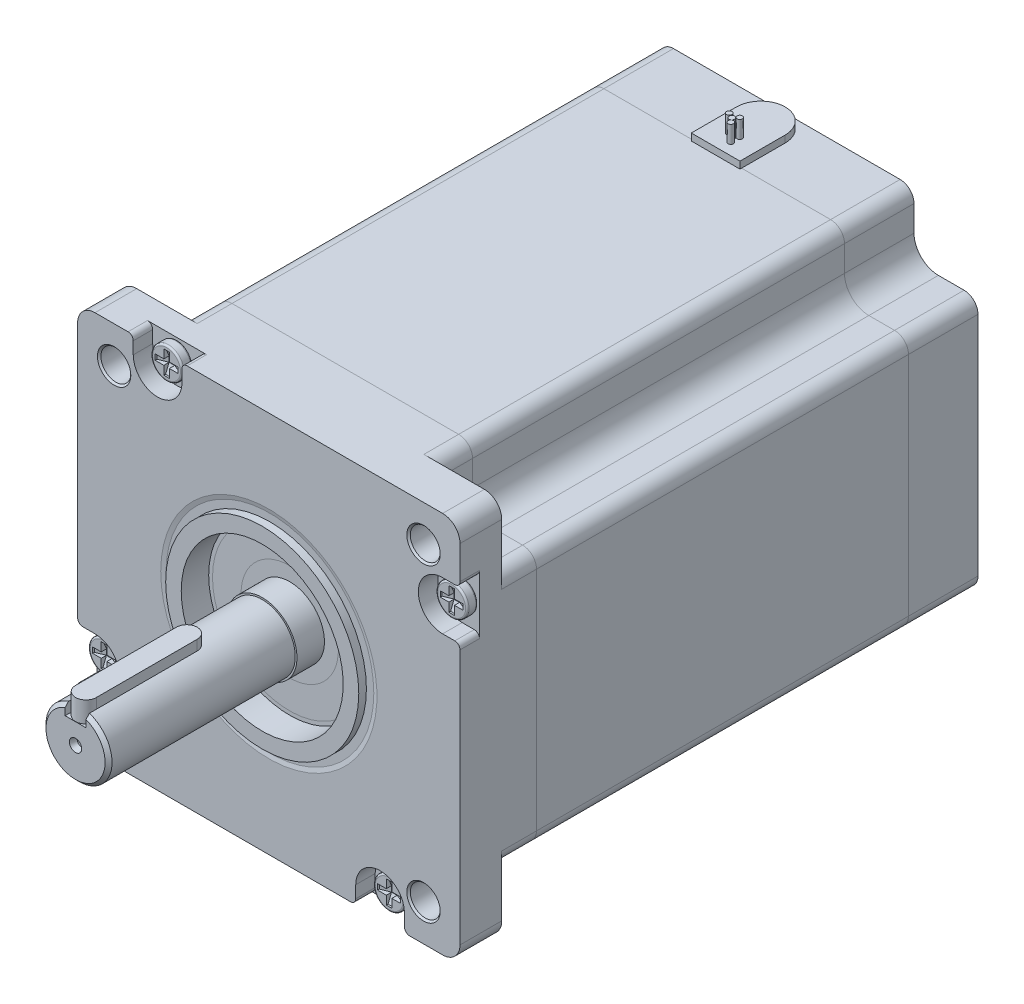
SolidWorks part; units mm, degrees
ref_plane "Front Plane" through (0, 0, 0) normal (0, 0, 1) x (1, 0, 0)
ref_plane "Top Plane" through (0, 0, 0) normal (0, 1, 0) x (1, 0, 0)
ref_plane "Right Plane" through (0, 0, 0) normal (1, 0, 0) x (0, 0, -1)
sketch "Sketch1" plane through (0, 0, 0) normal (0, 0, 1) x (1, 0, 0)
  line L1 (50, -55) -> (-50, -55)
  line L2 (55, -50) -> (55, 50)
  line L3 (50, 55) -> (-50, 55)
  line L4 (-55, -50) -> (-55, 50)
  line L5 (55, -55) -> (-55, 55) construction
  line L6 (55, 55) -> (-55, -55) construction
  arc A0 (50, -55) -> (55, -50) centre (50, -50) ccw
  arc A1 (-50, -55) -> (-55, -50) centre (-50, -50) cw
  arc A2 (55, 50) -> (50, 55) centre (50, 50) ccw
  arc A3 (-50, 55) -> (-55, 50) centre (-50, 50) ccw
  circle A4 centre (-44.5, 44.5) radius 4.3
  circle A5 centre (44.5, 44.5) radius 4.3
  circle A6 centre (-44.5, -44.5) radius 4.3
  circle A7 centre (44.5, -44.5) radius 4.3
  point P0 (0, 0)
  dimension "D3" = 5
  dimension "D4" = 8.6
  dimension "D5" = 89
  dimension "D6" = 89
  dimension "D1" = 110
  dimension "D2" = 110
  dimension "D7" = 44.5
  dimension "D8" = 44.5
extrude "Boss-Extrude1" add sketch "Sketch1" along normal blind 22
sketch "Sketch2" plane through (0, 0, 0) normal (0, 0, -1) x (-1, 0, 0)
  line L0 (-51, 36.6) -> (-43.6, 36.6)
  line L1 (-36.6, 43.6) -> (-36.6, 51)
  line L2 (-32.6, 55) -> (-50, 55)
  line L3 (-55, 50) -> (-55, 32.6)
  line L4 (-50, -55) -> (50, -55)
  line L5 (55, -50) -> (55, 50)
  line L6 (50, 55) -> (-50, 55)
  line L7 (-55, 50) -> (-55, -50)
  line L8 (0, 55) -> (0, -55) construction
  line L9 (-50, 55) -> (50, 55) construction
  line L10 (50, -55) -> (-50, -55) construction
  line L11 (0, 0) -> (-55, 0) construction
  line L12 (-55, -50) -> (-55, 50) construction
  line L13 (55, 50) -> (55, 32.6)
  line L14 (32.6, 55) -> (50, 55)
  line L15 (36.6, 43.6) -> (36.6, 51)
  line L16 (51, 36.6) -> (43.6, 36.6)
  line L17 (51, -36.6) -> (43.6, -36.6)
  line L18 (36.6, -43.6) -> (36.6, -51)
  line L19 (32.6, -55) -> (50, -55)
  line L20 (55, -50) -> (55, -32.6)
  line L21 (-55, -50) -> (-55, -32.6)
  line L22 (-32.6, -55) -> (-50, -55)
  line L23 (-36.6, -43.6) -> (-36.6, -51)
  line L24 (-51, -36.6) -> (-43.6, -36.6)
  arc A0 (-43.6, 36.6) -> (-36.6, 43.6) centre (-43.6, 43.6) ccw
  arc A1 (-51, 36.6) -> (-55, 32.6) centre (-51, 32.6) ccw
  arc A2 (-36.6, 51) -> (-32.6, 55) centre (-32.6, 51) cw
  arc A3 (50, 55) -> (55, 50) centre (50, 50) cw
  arc A4 (-55, -50) -> (-50, -55) centre (-50, -50) ccw
  arc A5 (50, -55) -> (55, -50) centre (50, -50) ccw
  arc A6 (55, 50) -> (50, 55) centre (50, 50) ccw
  arc A7 (-50, 55) -> (-55, 50) centre (-50, 50) ccw
  arc A8 (36.6, 51) -> (32.6, 55) centre (32.6, 51) ccw
  arc A9 (51, 36.6) -> (55, 32.6) centre (51, 32.6) cw
  arc A10 (43.6, 36.6) -> (36.6, 43.6) centre (43.6, 43.6) cw
  arc A11 (-50, 55) -> (-55, 50) centre (-50, 50) ccw
  arc A12 (43.6, -36.6) -> (36.6, -43.6) centre (43.6, -43.6) ccw
  arc A13 (51, -36.6) -> (55, -32.6) centre (51, -32.6) ccw
  arc A14 (36.6, -51) -> (32.6, -55) centre (32.6, -51) cw
  arc A15 (50, -55) -> (55, -50) centre (50, -50) ccw
  arc A16 (-50, -55) -> (-55, -50) centre (-50, -50) cw
  arc A17 (-36.6, -51) -> (-32.6, -55) centre (-32.6, -51) ccw
  arc A18 (-51, -36.6) -> (-55, -32.6) centre (-51, -32.6) cw
  arc A19 (-43.6, -36.6) -> (-36.6, -43.6) centre (-43.6, -43.6) cw
  point P17 (-36.6, 36.6)
  point P20 (-55, 36.6)
  point P43 (55, 36.6)
  point P44 (36.6, 36.6)
  point P54 (36.6, -36.6)
  point P55 (55, -36.6)
  point P65 (-55, -36.6)
  point P66 (-36.6, -36.6)
  dimension "D4" = 7
  dimension "D5" = 4
  dimension "D3" = 18.4
  dimension "D1" = 0
extrude "Cut-Extrude1" cut sketch "Sketch2" against normal blind 10
chamfer "Chamfer1" distance 0.5 angle 45 8 edges at (-48.8, -44.5, 10) (-40.2, -44.5, 22) (48.8, -44.5, 22) (48.8, -44.5, 10) (40.2, 44.5, 10) (48.8, 44.5, 22) (-40.2, 44.5, 22) (-40.2, 44.5, 10)
sketch "Sketch3" plane through (0, 0, 22) normal (0, 0, 1) x (1, 0, 0)
  line L0 (50, 55) -> (-50, 55) construction
  line L1 (-39, 50) -> (-39, 60.5998)
  line L2 (-39, 60.5998) -> (-25, 60.5998)
  line L3 (-25, 60.5998) -> (-25, 50)
  line L4 (-55, 50) -> (-55, -50) construction
  arc A0 (-39, 50) -> (-25, 50) centre (-32, 50) ccw
  dimension "D2" = 14
  dimension "D1" = 5
  dimension "D3" = 16
extrude "Cut-Extrude2" cut sketch "Sketch3" against normal blind 5.6
fillet "Fillet1" radius 1.5 2 edges at (-39, 55, 19.2) (-25, 55, 19.2)
sketch "Sketch6" plane through (0, 0, 22) normal (0, 0, 1) x (1, 0, 0)
  circle A0 centre (0, 0) radius 27.775
  dimension "D1" = 55.55
extrude "Boss-Extrude2" add sketch "Sketch6" along normal blind 1.9
sketch "Sketch7" plane through (0, 0, 0) normal (1, 0, 0) x (0, 0, -1)
  line L0 (0, 0) -> (-55.0013, 0) construction
  line L1 (-22, 27.775) -> (-21.7, 27.775)
  line L2 (-22, -50) -> (-22, 50) construction
  line L3 (-22, 27.775) -> (-22, -27.775) construction
  line L4 (-21.7, 27.775) -> (-21.7, 29.9)
  line L5 (-21.7, 29.9) -> (-22, 31.1)
  line L6 (-22, 31.1) -> (-22, 27.775)
  line L7 (-23.9, 27.775) -> (-23.9, -27.775) construction
  line L8 (-23.9, 23.3) -> (-16, 23.3)
  line L9 (-16, 23.3) -> (-16, 10)
  line L10 (-16, 10) -> (-23.9, 10)
  line L11 (-23.9, 10) -> (-23.9, 23.3)
  dimension "D1" = 55.55
  dimension "D2" = 2.2
  dimension "D3" = 59.8
  dimension "D4" = 62.2
  dimension "D5" = 46.6
  dimension "D6" = 20
  dimension "D7" = 7.9
revolve "Cut-Revolve1" cut sketch "Sketch7" angle 360 about L0
sketch "Sketch8" plane through (0, 0, 16) normal (0, 0, 1) x (1, 0, 0)
  circle A0 centre (0, 0) radius 14
  circle A1 centre (0, 0) radius 22.2
  dimension "D1" = 28
  dimension "D2" = 44.4
split line "Split Line1"
sketch "Sketch9" plane through (0, 0, 23.9) normal (0, 0, 1) x (1, 0, 0)
  circle A0 centre (0, 0) radius 9.5
  dimension "D1" = 19
extrude "Boss-Extrude3" add sketch "Sketch9" along normal blind 53.7
chamfer "Chamfer2" distance 1 angle 45 1 edges at (9.5, 0, 77.6)
sketch "Sketch11" plane through (0, 0, 77.6) normal (0, 0, 1) x (1, 0, 0)
  line L1 (3, 13.1) -> (-3, 13.1)
  line L2 (3, 13.1) -> (3, 5.9)
  line L3 (3, 5.9) -> (-3, 5.9)
  line L4 (-3, 13.1) -> (-3, 5.9)
  line L5 (3, 13.1) -> (-3, 5.9) construction
  line L6 (3, 5.9) -> (-3, 13.1) construction
  circle A0 centre (0, 0) radius 9.5 construction
  circle A1 centre (0, 0) radius 9.5 construction
  point P0 (0, 9.5)
  dimension "D1" = 6
  dimension "D2" = 3.6
extrude "Cut-Extrude3" cut sketch "Sketch11" against normal blind 35
fillet "Fillet2" radius 2.95 2 edges at (-3, 7.4569, 42.6) (3, 7.4569, 42.6)
sketch "Sketch12" plane through (0, 5.9, 0) normal (0, 1, 0) x (1, 0, 0)
  line L0 (-0.05, -45.55) -> (-0.05, -74.55) construction
  line L1 (2.95, -45.55) -> (2.95, -74.55)
  line L2 (-3.05, -45.55) -> (-3.05, -74.55)
  arc A0 (2.95, -45.55) -> (-3.05, -45.55) centre (-0.05, -45.55) ccw
  arc A1 (-3.05, -74.55) -> (2.95, -74.55) centre (-0.05, -74.55) ccw
  point P3 (-0.05, -60.05)
  dimension "D2" = 3
  dimension "D1" = 29
extrude "Boss-Extrude4" add sketch "Sketch12" along normal blind 6 separate body
sketch "Sketch13" plane through (0, 0, 77.6) normal (0, 0, 1) x (1, 0, 0)
  circle A0 centre (0, 0) radius 1.2695
extrude "Cut-Extrude4" cut sketch "Sketch13" against normal blind 5
chamfer "Chamfer3" distance 0.5 angle 74 1 edges at (1.2695, 0, 77.6)
pattern_circular "CirPattern2" count 4 over 360 about axis through (0, 0, 0) along (0, 0, 1) of "Cut-Extrude2"
fillet "Fillet3" radius 1.5 6 edges at (-55, -39, 19.2) (-55, -25, 19.2) (39, -55, 19.2) (25, -55, 19.2) (55, 25, 19.2) (55, 39, 19.2)
sketch "Sketch14" plane through (0, 0, 16.4) normal (0, 0, 1) x (1, 0, 0)
  circle A0 centre (-32, 50) radius 4.5
  dimension "D1" = 9
extrude "Boss-Extrude5" add sketch "Sketch14" along normal blind 3 separate body
fillet "Fillet4" radius 0.5 2 edges at (-27.5, 50, 16.4) (-27.5, 50, 19.4)
sketch "Sketch15" plane through (0, 0, 19.4) normal (0, 0, 1) x (1, 0, 0)
  line L0 (-31.2058, 50.8067) -> (-28.6738, 50.8067)
  line L1 (-32.7942, 46.7257) -> (-31.2058, 46.7257)
  line L2 (-32.7942, 46.7257) -> (-32.7942, 49.1933)
  line L3 (-32.7942, 53.2743) -> (-31.2058, 53.2743)
  line L4 (-31.2058, 46.7257) -> (-31.2058, 49.1933)
  line L7 (-35.3262, 49.1933) -> (-32.7942, 49.1933)
  line L8 (-35.3262, 49.1933) -> (-35.3262, 50.8067)
  line L9 (-35.3262, 50.8067) -> (-32.7942, 50.8067)
  line L10 (-28.6738, 49.1933) -> (-28.6738, 50.8067)
  line L15 (-31.2058, 49.1933) -> (-28.6738, 49.1933)
  line L18 (-32.7942, 50.8067) -> (-32.7942, 53.2743)
  line L19 (-31.2058, 50.8067) -> (-31.2058, 53.2743)
  point P0 (-32, 50)
  point P6 (-32, 50)
extrude "Cut-Extrude5" cut sketch "Sketch15" against normal blind 1.5
chamfer "Chamfer4" distance 1 angle 68 4 edges at (-32, 46.7257, 17.9) (-32, 53.2743, 17.9) (-35.3262, 50, 17.9) (-28.6738, 50, 17.9)
pattern_circular "CirPattern3" count 4 over 360 about axis through (0, 0, 0) along (0, 0, 1) of bodies 113
sketch "Sketch16" plane through (0, 0, 0) normal (0, 0, -1) x (-1, 0, 0)
  line L12 (55, -32.6) -> (55, 32.6)
  line L13 (51, 36.6) -> (43.6, 36.6)
  line L14 (36.6, 43.6) -> (36.6, 51)
  line L15 (32.6, 55) -> (-32.6, 55)
  line L16 (-36.6, 51) -> (-36.6, 43.6)
  line L17 (-43.6, 36.6) -> (-51, 36.6)
  line L18 (-55, 32.6) -> (-55, -32.6)
  line L19 (-51, -36.6) -> (-43.6, -36.6)
  line L20 (-36.6, -43.6) -> (-36.6, -51)
  line L21 (-32.6, -55) -> (32.6, -55)
  line L22 (36.6, -51) -> (36.6, -43.6)
  line L23 (43.6, -36.6) -> (51, -36.6)
  line L24 (55, -32.6) -> (55, 32.6)
  line L25 (51, 36.6) -> (43.6, 36.6)
  line L26 (36.6, 43.6) -> (36.6, 51)
  line L27 (32.6, 55) -> (-32.6, 55)
  line L28 (-36.6, 51) -> (-36.6, 43.6)
  line L29 (-43.6, 36.6) -> (-51, 36.6)
  line L30 (-55, 32.6) -> (-55, -32.6)
  line L31 (-51, -36.6) -> (-43.6, -36.6)
  line L32 (-36.6, -43.6) -> (-36.6, -51)
  line L33 (-32.6, -55) -> (32.6, -55)
  line L34 (36.6, -51) -> (36.6, -43.6)
  line L35 (43.6, -36.6) -> (51, -36.6)
  arc A12 (55, 32.6) -> (51, 36.6) centre (51, 32.6) ccw
  arc A13 (36.6, 43.6) -> (43.6, 36.6) centre (43.6, 43.6) ccw
  arc A14 (36.6, 51) -> (32.6, 55) centre (32.6, 51) ccw
  arc A15 (-32.6, 55) -> (-36.6, 51) centre (-32.6, 51) ccw
  arc A16 (-43.6, 36.6) -> (-36.6, 43.6) centre (-43.6, 43.6) ccw
  arc A17 (-51, 36.6) -> (-55, 32.6) centre (-51, 32.6) ccw
  arc A18 (-55, -32.6) -> (-51, -36.6) centre (-51, -32.6) ccw
  arc A19 (-36.6, -43.6) -> (-43.6, -36.6) centre (-43.6, -43.6) ccw
  arc A20 (-36.6, -51) -> (-32.6, -55) centre (-32.6, -51) ccw
  arc A21 (32.6, -55) -> (36.6, -51) centre (32.6, -51) ccw
  arc A22 (43.6, -36.6) -> (36.6, -43.6) centre (43.6, -43.6) ccw
  arc A23 (51, -36.6) -> (55, -32.6) centre (51, -32.6) ccw
  arc A24 (55, 32.6) -> (51, 36.6) centre (51, 32.6) ccw
  arc A25 (36.6, 43.6) -> (43.6, 36.6) centre (43.6, 43.6) ccw
  arc A26 (36.6, 51) -> (32.6, 55) centre (32.6, 51) ccw
  arc A27 (-32.6, 55) -> (-36.6, 51) centre (-32.6, 51) ccw
  arc A28 (-43.6, 36.6) -> (-36.6, 43.6) centre (-43.6, 43.6) ccw
  arc A29 (-51, 36.6) -> (-55, 32.6) centre (-51, 32.6) ccw
  arc A30 (-55, -32.6) -> (-51, -36.6) centre (-51, -32.6) ccw
  arc A31 (-36.6, -43.6) -> (-43.6, -36.6) centre (-43.6, -43.6) ccw
  arc A32 (-36.6, -51) -> (-32.6, -55) centre (-32.6, -51) ccw
  arc A33 (32.6, -55) -> (36.6, -51) centre (32.6, -51) ccw
  arc A34 (43.6, -36.6) -> (36.6, -43.6) centre (43.6, -43.6) ccw
  arc A35 (51, -36.6) -> (55, -32.6) centre (51, -32.6) ccw
  dimension "D1" = 0
extrude "Boss-Extrude6" add sketch "Sketch16" along normal blind 107 separate body
sketch "Sketch17" plane through (0, 0, -107) normal (0, 0, -1) x (-1, 0, 0)
  line L12 (55, -32.6) -> (55, 32.6)
  line L13 (51, 36.6) -> (43.6, 36.6)
  line L14 (36.6, 43.6) -> (36.6, 51)
  line L15 (32.6, 55) -> (-32.6, 55)
  line L16 (-36.6, 51) -> (-36.6, 43.6)
  line L17 (-43.6, 36.6) -> (-51, 36.6)
  line L18 (-55, 32.6) -> (-55, -32.6)
  line L19 (-51, -36.6) -> (-43.6, -36.6)
  line L20 (-36.6, -43.6) -> (-36.6, -51)
  line L21 (-32.6, -55) -> (32.6, -55)
  line L22 (36.6, -51) -> (36.6, -43.6)
  line L23 (43.6, -36.6) -> (51, -36.6)
  line L24 (55, -32.6) -> (55, 32.6)
  line L25 (51, 36.6) -> (43.6, 36.6)
  line L26 (36.6, 43.6) -> (36.6, 51)
  line L27 (32.6, 55) -> (-32.6, 55)
  line L28 (-36.6, 51) -> (-36.6, 43.6)
  line L29 (-43.6, 36.6) -> (-51, 36.6)
  line L30 (-55, 32.6) -> (-55, -32.6)
  line L31 (-51, -36.6) -> (-43.6, -36.6)
  line L32 (-36.6, -43.6) -> (-36.6, -51)
  line L33 (-32.6, -55) -> (32.6, -55)
  line L34 (36.6, -51) -> (36.6, -43.6)
  line L35 (43.6, -36.6) -> (51, -36.6)
  arc A12 (51, -36.6) -> (55, -32.6) centre (51, -32.6) ccw
  arc A13 (55, 32.6) -> (51, 36.6) centre (51, 32.6) ccw
  arc A14 (36.6, 43.6) -> (43.6, 36.6) centre (43.6, 43.6) ccw
  arc A15 (36.6, 51) -> (32.6, 55) centre (32.6, 51) ccw
  arc A16 (-32.6, 55) -> (-36.6, 51) centre (-32.6, 51) ccw
  arc A17 (-43.6, 36.6) -> (-36.6, 43.6) centre (-43.6, 43.6) ccw
  arc A18 (-51, 36.6) -> (-55, 32.6) centre (-51, 32.6) ccw
  arc A19 (-55, -32.6) -> (-51, -36.6) centre (-51, -32.6) ccw
  arc A20 (-36.6, -43.6) -> (-43.6, -36.6) centre (-43.6, -43.6) ccw
  arc A21 (-36.6, -51) -> (-32.6, -55) centre (-32.6, -51) ccw
  arc A22 (32.6, -55) -> (36.6, -51) centre (32.6, -51) ccw
  arc A23 (43.6, -36.6) -> (36.6, -43.6) centre (43.6, -43.6) ccw
  arc A24 (51, -36.6) -> (55, -32.6) centre (51, -32.6) ccw
  arc A25 (55, 32.6) -> (51, 36.6) centre (51, 32.6) ccw
  arc A26 (36.6, 43.6) -> (43.6, 36.6) centre (43.6, 43.6) ccw
  arc A27 (36.6, 51) -> (32.6, 55) centre (32.6, 51) ccw
  arc A28 (-32.6, 55) -> (-36.6, 51) centre (-32.6, 51) ccw
  arc A29 (-43.6, 36.6) -> (-36.6, 43.6) centre (-43.6, 43.6) ccw
  arc A30 (-51, 36.6) -> (-55, 32.6) centre (-51, 32.6) ccw
  arc A31 (-55, -32.6) -> (-51, -36.6) centre (-51, -32.6) ccw
  arc A32 (-36.6, -43.6) -> (-43.6, -36.6) centre (-43.6, -43.6) ccw
  arc A33 (-36.6, -51) -> (-32.6, -55) centre (-32.6, -51) ccw
  arc A34 (32.6, -55) -> (36.6, -51) centre (32.6, -51) ccw
  arc A35 (43.6, -36.6) -> (36.6, -43.6) centre (43.6, -43.6) ccw
  dimension "D1" = 0
extrude "Boss-Extrude7" add sketch "Sketch17" along normal blind 20 separate body
sketch "Sketch18" plane through (0, 0, -127) normal (0, 0, -1) x (-1, 0, 0)
  circle A0 centre (0, 0) radius 17.5
  dimension "D1" = 35
extrude "Cut-Extrude6" cut sketch "Sketch18" against normal blind 4.6
sketch "Sketch19" plane through (0, 55, 0) normal (0, 1, 0) x (1, 0, 0)
  line L0 (0, 127) -> (0, 112.5319) construction
  line L1 (-32.6, 127) -> (32.6, 127) construction
  line L2 (-7, 119.5319) -> (-7, 106.5319)
  line L3 (-7, 106.5319) -> (7, 106.5319)
  line L4 (7, 106.5319) -> (7, 119.5319)
  line L5 (0, 106.5319) -> (0, 90.3404) construction
  arc A0 (7, 119.5319) -> (-7, 119.5319) centre (0, 119.5319) ccw
  dimension "D1" = 14
  dimension "D2" = 13
extrude "Boss-Extrude8" add sketch "Sketch19" along normal blind 2 separate body
sketch "Sketch20" plane through (0, 57, 0) normal (0, 1, 0) x (1, 0, 0)
  circle A0 centre (-1.528, 111.9593) radius 0.7818
  circle A1 centre (0, 111.1776) radius 0.7818
  circle A2 centre (1.0664, 112.3932) radius 0.7557
  circle A3 centre (0.9858, 109.9174) radius 0.7776
extrude "Boss-Extrude9" add sketch "Sketch20" along normal blind 5
